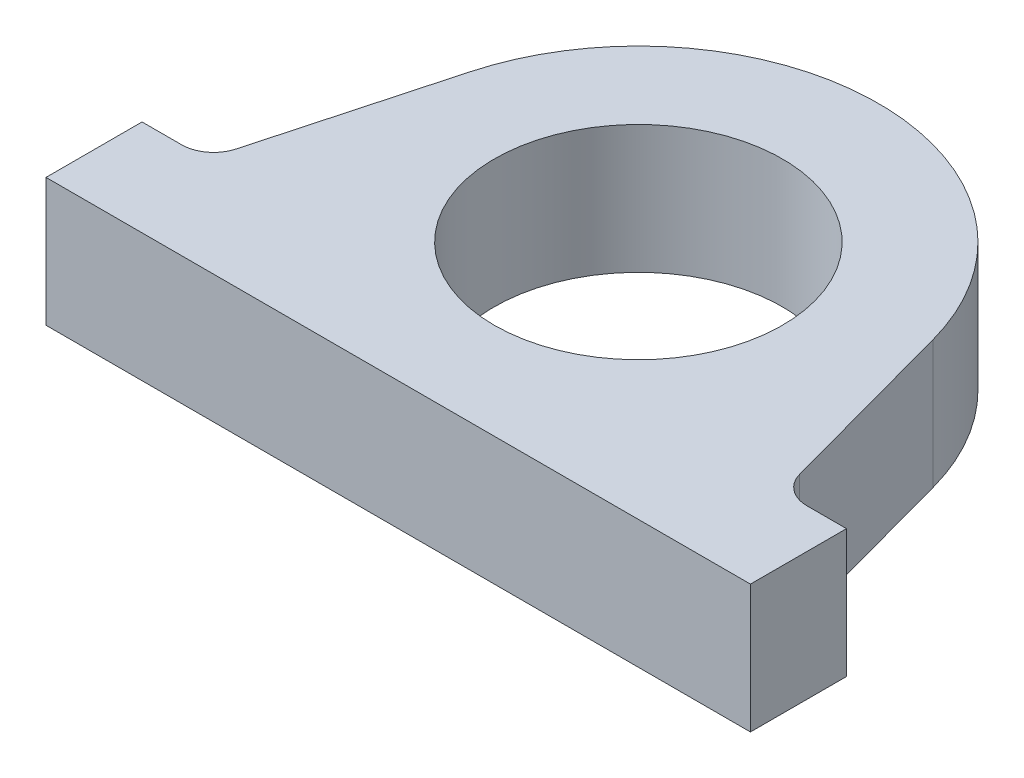
SolidWorks part; units mm, degrees
ref_plane "前视基准面" through (0, 0, 0) normal (0, 0, 1) x (1, 0, 0)
ref_plane "上视基准面" through (0, 0, 0) normal (0, 1, 0) x (1, 0, 0)
ref_plane "右视基准面" through (0, 0, 0) normal (1, 0, 0) x (0, 0, -1)
sketch "草图1" plane through (0, 0, 0) normal (0, 1, 0) x (1, 0, 0)
  line L0 (110, 0) -> (-110, 0)
  line L1 (-110, 0) -> (-110, 30)
  line L2 (-110, 30) -> (-90, 30)
  line L3 (-90, 30) -> (-72.3607, 94.7214)
  line L4 (0, 0) -> (0, 54.1877) construction
  line L5 (90, 30) -> (72.3607, 94.7214)
  line L6 (110, 30) -> (90, 30)
  line L7 (110, 0) -> (110, 30)
  arc A0 (-72.3607, 94.7214) -> (72.3607, 94.7214) centre (0, 75) cw
  circle A1 centre (0, 75) radius 45
  point P12 (-80, 16.9412)
  point P13 (0, 150)
  point P14 (-57.1433, 78.2933)
  dimension "D4" = 90
  dimension "D1" = 220
  dimension "D2" = 75
  dimension "D3" = 150
  dimension "D5" = 20
  dimension "D6" = 30
extrude "凸台-拉伸1" add sketch "草图1" along normal blind 40
fillet "圆角1" radius 10 2 edges at (-90, 20, -30) (90, 20, -30)
